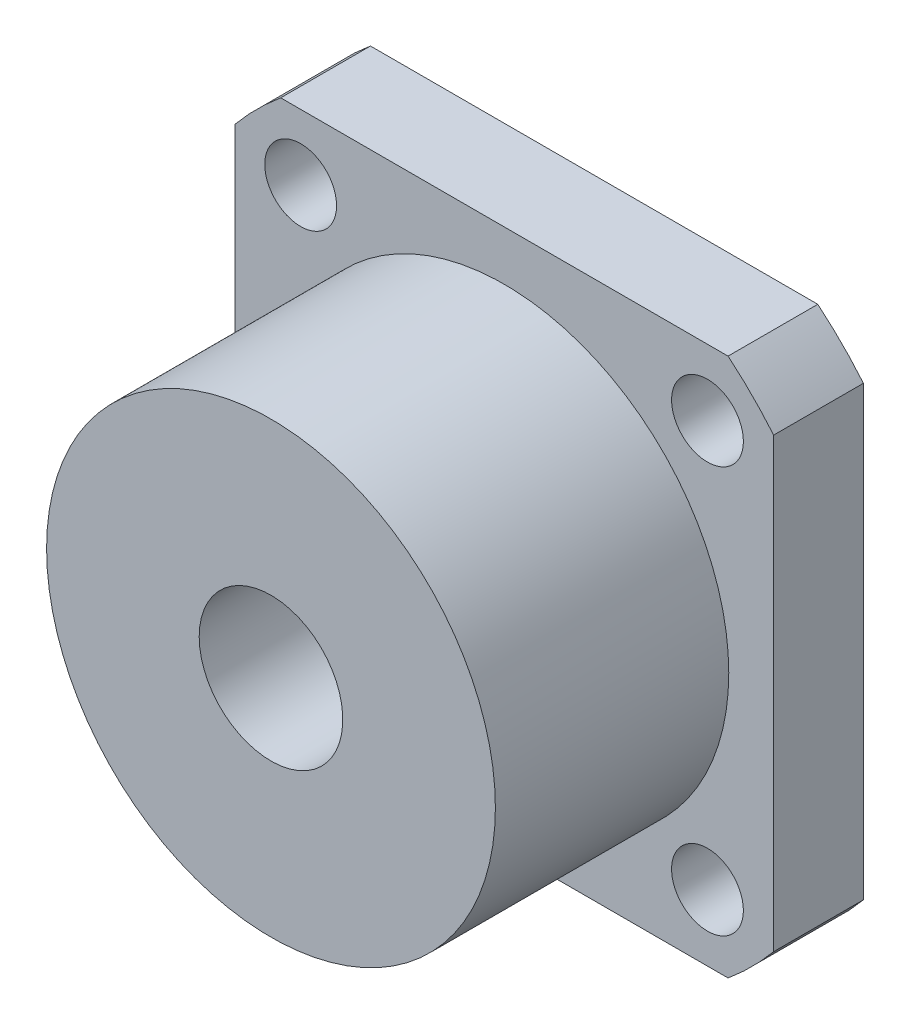
SolidWorks part; units mm, degrees
ref_plane "前视基准面" through (0, 0, 0) normal (0, 0, 1) x (1, 0, 0)
ref_plane "上视基准面" through (0, 0, 0) normal (0, 1, 0) x (1, 0, 0)
ref_plane "右视基准面" through (0, 0, 0) normal (1, 0, 0) x (0, 0, -1)
sketch "草图1" plane through (0, 0, 0) normal (0, 0, 1) x (1, 0, 0)
  line L1 (-12.4599, -14.7363) -> (12.4599, -14.7363)
  line L2 (-15, -12.1963) -> (-15, 12.7236)
  line L3 (-12.4599, 15.2637) -> (12.4599, 15.2637)
  line L4 (15, -12.1963) -> (15, 12.7236)
  line L5 (-15, -14.7363) -> (15, 15.2637) construction
  line L6 (-15, 15.2637) -> (15, -14.7363) construction
  circle A0 centre (0, 0.2637) radius 19.5 construction
  arc A1 (-15, 12.7236) -> (-12.4599, 15.2637) centre (0, 0.2637) cw
  arc A2 (-12.4599, -14.7363) -> (-15, -12.1963) centre (0, 0.2637) cw
  arc A4 (12.4599, 15.2637) -> (15, 12.7236) centre (0, 0.2637) cw
  arc A5 (15, -12.1963) -> (12.4599, -14.7363) centre (0, 0.2637) cw
  circle A6 centre (0, 0.2637) radius 16 construction
  circle A7 centre (-11.3476, 11.6113) radius 2
  circle A8 centre (11.3137, 11.5774) radius 2
  circle A9 centre (11.3137, -11.05) radius 2
  circle A10 centre (-11.3137, -11.05) radius 2
  point P0 (0, 0.2637)
  dimension "D3" = 39
  dimension "D4" = 32
  dimension "D5" = 4
  dimension "D6" = 4
  dimension "D7" = 4
  dimension "D8" = 4
  dimension "D1" = 30
  dimension "D2" = 30
extrude "凸台-拉伸1" add sketch "草图1" along normal blind 5
sketch "草图3" plane through (0, 0, 5) normal (0, 0, 1) x (1, 0, 0)
  circle A0 centre (0, 0) radius 4
  circle A1 centre (0, 0) radius 12.5
  dimension "D1" = 25
  dimension "D2" = 8
extrude "凸台-拉伸2" add sketch "草图3" along normal blind 13
sketch "草图5" plane through (0, 0, 5) normal (0, 0, 1) x (1, 0, 0)
  circle A0 centre (0, 0) radius 4
  dimension "D1" = 8
extrude "切除-拉伸1" cut sketch "草图5" against normal through all
